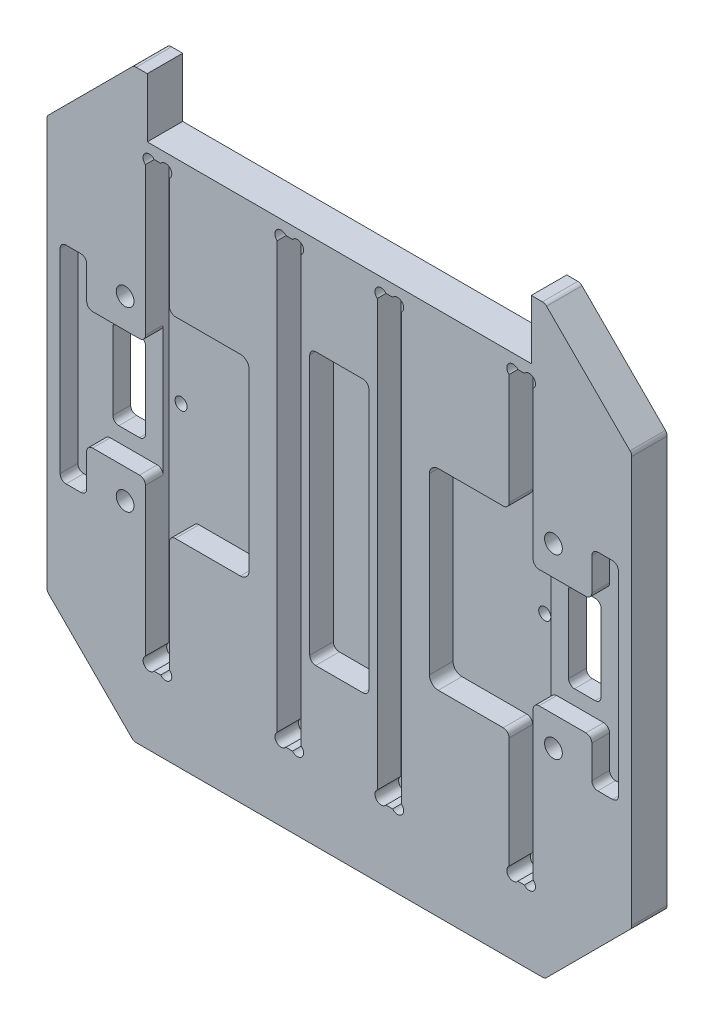
SolidWorks part; units mm, degrees
ref_plane "Front" through (0, 0, 0) normal (0, 0, 1) x (1, 0, 0)
ref_plane "Top" through (0, 0, 0) normal (0, 1, 0) x (1, 0, 0)
ref_plane "Right" through (0, 0, 0) normal (1, 0, 0) x (0, 0, -1)
sketch "Esquisse2" plane through (0, 0, 0) normal (0, 0, 1) x (1, 0, 0)
  line L1 (0, 0) -> (200, 0)
  line L2 (0, 0) -> (0, 200)
  line L3 (0, 200) -> (200, 200)
  line L4 (200, 0) -> (200, 200)
  dimension "D1" = 200
  dimension "D2" = 200
extrude "Boss.-Extru.1" add sketch "Esquisse2" along normal blind 12
chamfer "Chanfrein1" distance 30 distance2 30 4 edges at (0, 200, 6) (200, 200, 6) (200, 0, 6) (0, 0, 6)
sketch "Esquisse3" plane through (0, 0, 12) normal (0, 0, 1) x (1, 0, 0)
  line L0 (0, 100) -> (200, 100) construction
  line L1 (0, 170) -> (0, 30) construction
  line L2 (200, 30) -> (200, 170) construction
  line L3 (30, 0) -> (170, 0) construction
  line L4 (100, 100) -> (100, 198.2097) construction
  line L5 (185.5, 67) -> (185.5, 133)
  line L6 (187.5, 135) -> (192.5, 135)
  line L7 (194.5, 133) -> (194.5, 67)
  line L8 (187.5, 65) -> (192.5, 65)
  line L9 (12.5, 65) -> (7.5, 65)
  line L10 (5.5, 133) -> (5.5, 67)
  line L11 (12.5, 135) -> (7.5, 135)
  line L12 (14.5, 67) -> (14.5, 133)
  line L13 (69.5, 70.5) -> (69.5, 129.5)
  line L14 (66.5, 132.5) -> (45.5, 132.5)
  line L15 (42.5, 129.5) -> (42.5, 70.5)
  line L16 (190, 135) -> (190, 163.9784) construction
  line L17 (190, 163.9784) -> (100, 163.9784) construction
  line L18 (56, 132.5) -> (56, 150.9164) construction
  line L19 (56, 150.9164) -> (100, 150.9164) construction
  line L20 (66.5, 67.5) -> (45.5, 67.5)
  line L21 (133.5, 67.5) -> (154.5, 67.5)
  line L22 (157.5, 129.5) -> (157.5, 70.5)
  line L23 (133.5, 132.5) -> (154.5, 132.5)
  line L24 (130.5, 70.5) -> (130.5, 129.5)
  circle A0 centre (172.5, 130) radius 3
  circle A1 centre (172.5, 70) radius 3
  circle A2 centre (27.5, 70) radius 3
  circle A3 centre (27.5, 130) radius 3
  arc A4 (192.5, 65) -> (194.5, 67) centre (192.5, 67) ccw
  arc A5 (187.5, 65) -> (185.5, 67) centre (187.5, 67) cw
  arc A6 (192.5, 135) -> (194.5, 133) centre (192.5, 133) cw
  arc A7 (185.5, 133) -> (187.5, 135) centre (187.5, 133) cw
  arc A8 (12.5, 65) -> (14.5, 67) centre (12.5, 67) ccw
  arc A9 (7.5, 65) -> (5.5, 67) centre (7.5, 67) cw
  arc A10 (12.5, 135) -> (14.5, 133) centre (12.5, 133) cw
  arc A11 (5.5, 133) -> (7.5, 135) centre (7.5, 133) cw
  arc A12 (133.5, 67.5) -> (130.5, 70.5) centre (133.5, 70.5) cw
  arc A13 (154.5, 67.5) -> (157.5, 70.5) centre (154.5, 70.5) ccw
  arc A14 (157.5, 129.5) -> (154.5, 132.5) centre (154.5, 129.5) ccw
  arc A15 (133.5, 132.5) -> (130.5, 129.5) centre (133.5, 129.5) ccw
  arc A16 (66.5, 67.5) -> (69.5, 70.5) centre (66.5, 70.5) ccw
  arc A17 (45.5, 67.5) -> (42.5, 70.5) centre (45.5, 70.5) cw
  arc A18 (69.5, 129.5) -> (66.5, 132.5) centre (66.5, 129.5) ccw
  arc A19 (45.5, 132.5) -> (42.5, 129.5) centre (45.5, 129.5) ccw
  point P23 (194.5, 100)
  point P24 (185.5, 100)
  point P28 (14.5, 100)
  point P29 (5.5, 100)
  point P41 (42.5, 100)
  point P42 (69.5, 100)
  point P46 (130.5, 100)
  point P47 (157.5, 100)
  point P50 (194.5, 65)
  point P53 (185.5, 65)
  point P56 (194.5, 135)
  point P59 (185.5, 135)
  point P62 (14.5, 65)
  point P65 (5.5, 65)
  point P68 (14.5, 135)
  point P71 (5.5, 135)
  point P74 (130.5, 67.5)
  point P77 (157.5, 67.5)
  point P80 (157.5, 132.5)
  point P83 (130.5, 132.5)
  point P86 (69.5, 67.5)
  point P89 (42.5, 67.5)
  point P92 (69.5, 132.5)
  point P95 (42.5, 132.5)
  dimension "D2" = 60
  dimension "D3" = 44
  dimension "D4" = 6
  dimension "D11" = 2
  dimension "D12" = 3
  dimension "D1" = 100
  dimension "D5" = 9
  dimension "D6" = 13
  dimension "D7" = 70
  dimension "D8" = 90
  dimension "D9" = 65
  dimension "D10" = 27
extrude "Enlèv. mat.-Extru.1" cut sketch "Esquisse3" against normal through all both and the other way through all
sketch "Esquisse4" plane through (0, 0, 12) normal (0, 0, 1) x (1, 0, 0)
  line L16 (169.5858, 199) -> (30.4142, 199)
  line L17 (30.4142, 199) -> (1, 169.5858)
  line L18 (1, 169.5858) -> (1, 30.4142)
  line L19 (1, 30.4142) -> (30.4142, 1)
  line L20 (30.4142, 1) -> (169.5858, 1)
  line L21 (169.5858, 1) -> (199, 30.4142)
  line L22 (199, 30.4142) -> (199, 169.5858)
  line L23 (199, 169.5858) -> (169.5858, 199)
  line L24 (169.5858, 199) -> (30.4142, 199)
  line L25 (30.4142, 199) -> (1, 169.5858)
  line L26 (1, 169.5858) -> (1, 30.4142)
  line L27 (1, 30.4142) -> (30.4142, 1)
  line L28 (30.4142, 1) -> (169.5858, 1)
  line L29 (169.5858, 1) -> (199, 30.4142)
  line L30 (199, 30.4142) -> (199, 169.5858)
  line L31 (199, 169.5858) -> (169.5858, 199)
  line L32 (170, 200) -> (30, 200)
  line L33 (30, 200) -> (0, 170)
  line L34 (0, 170) -> (0, 30)
  line L35 (0, 30) -> (30, 0)
  line L36 (30, 0) -> (170, 0)
  line L37 (170, 0) -> (200, 30)
  line L38 (200, 30) -> (200, 170)
  line L39 (200, 170) -> (170, 200)
  line L40 (170, 200) -> (30, 200)
  line L41 (30, 200) -> (0, 170)
  line L42 (0, 170) -> (0, 30)
  line L43 (0, 30) -> (30, 0)
  line L44 (30, 0) -> (170, 0)
  line L45 (170, 0) -> (200, 30)
  line L46 (200, 30) -> (200, 170)
  line L47 (200, 170) -> (170, 200)
  dimension "D1" = 1
  dimension "D2" = 0
extrude "Enlèv. mat.-Extru.2" cut sketch "Esquisse4" against normal blind 10
sketch "Esquisse5" plane through (0, 0, 12) normal (0, 0, 1) x (1, 0, 0)
  line L0 (100, 0) -> (100, 100) construction
  line L1 (14.5, 120) -> (14.5, 80)
  line L2 (165.5, 120) -> (185.5, 120)
  line L3 (165.5, 120) -> (165.5, 80)
  line L4 (165.5, 80) -> (185.5, 80)
  line L5 (30, 0) -> (170, 0) construction
  line L6 (100, 100) -> (165.5, 100) construction
  line L7 (185.5, 120) -> (185.5, 80)
  line L8 (100, 100) -> (69.5, 100) construction
  line L9 (69.5, 70.5) -> (69.5, 129.5) construction
  line L10 (34.5, 80) -> (14.5, 80)
  line L11 (34.5, 120) -> (34.5, 80)
  line L12 (34.5, 120) -> (14.5, 120)
  dimension "D1" = 40
  dimension "D2" = 65.5
  dimension "D3" = 20
extrude "Enlèv. mat.-Extru.3" cut sketch "Esquisse5" against normal blind 6
sketch "Esquisse6" plane through (0, 0, 12) normal (0, 0, 1) x (1, 0, 0)
  line L0 (69.5, 100) -> (130.5, 100) construction
  line L1 (157.5, 175) -> (165.62, 175)
  line L2 (157.5, 175) -> (157.5, 25)
  line L3 (157.5, 25) -> (165.62, 25)
  line L4 (165.62, 175) -> (165.62, 25)
  line L5 (69.5, 70.5) -> (69.5, 129.5) construction
  line L6 (130.5, 129.5) -> (130.5, 70.5) construction
  line L7 (100, 100) -> (100, 191.362) construction
  line L8 (130.5, 100) -> (157.5, 100) construction
  line L9 (157.5, 70.5) -> (157.5, 129.5) construction
  line L10 (34.38, 175) -> (34.38, 25)
  line L11 (42.5, 25) -> (34.38, 25)
  line L12 (42.5, 175) -> (42.5, 25)
  line L13 (42.5, 175) -> (34.38, 175)
  line L14 (112.88, 100) -> (100, 100) construction
  line L15 (112.88, 175) -> (121, 175)
  line L16 (112.88, 175) -> (112.88, 25)
  line L17 (112.88, 25) -> (121, 25)
  line L18 (121, 175) -> (121, 25)
  line L19 (79, 175) -> (79, 25)
  line L20 (87.12, 25) -> (79, 25)
  line L21 (87.12, 175) -> (87.12, 25)
  line L22 (87.12, 175) -> (79, 175)
  dimension "D1" = 150
  dimension "D2" = 8.12
  dimension "D3" = 8.12
  dimension "D4" = 150
  dimension "D5" = 21
extrude "Enlèv. mat.-Extru.4" cut sketch "Esquisse6" against normal blind 8
sketch "Esquisse7" plane through (0, 0, 12) normal (0, 0, 1) x (1, 0, 0)
  line L0 (87.12, 100) -> (112.88, 100) construction
  line L1 (87.12, 25) -> (87.12, 175) construction
  line L2 (112.88, 175) -> (112.88, 25) construction
  line L3 (100, 100) -> (100, 199) construction
  line L4 (169.5858, 199) -> (30.4142, 199) construction
  line L5 (114.18, 173.7) -> (112.88, 175) construction
  line L6 (121, 175) -> (112.88, 175) construction
  line L7 (116.94, 175) -> (116.94, 100) construction
  line L8 (121, 175) -> (112.88, 175) construction
  line L9 (116.94, 100) -> (112.88, 100) construction
  line L10 (119.7, 173.7) -> (121, 175) construction
  line L11 (119.7, 26.3) -> (121, 25) construction
  line L12 (114.18, 26.3) -> (112.88, 25) construction
  line L13 (116.94, 100) -> (139.25, 100) construction
  line L14 (139.25, 100) -> (139.25, 192.3771) construction
  line L15 (164.32, 26.3) -> (165.62, 25) construction
  line L16 (158.8, 26.3) -> (157.5, 25) construction
  line L17 (158.8, 173.7) -> (157.5, 175) construction
  line L18 (161.56, 100) -> (165.62, 100) construction
  line L19 (161.56, 175) -> (161.56, 100) construction
  line L20 (164.32, 173.7) -> (165.62, 175) construction
  line L21 (165.62, 175) -> (157.5, 175) construction
  line L22 (35.68, 173.7) -> (34.38, 175) construction
  line L23 (38.44, 175) -> (38.44, 100) construction
  line L24 (38.44, 100) -> (34.38, 100) construction
  line L25 (41.2, 173.7) -> (42.5, 175) construction
  line L26 (41.2, 26.3) -> (42.5, 25) construction
  line L27 (35.68, 26.3) -> (34.38, 25) construction
  line L28 (60.75, 100) -> (60.75, 192.3771) construction
  line L29 (83.06, 100) -> (60.75, 100) construction
  line L30 (85.82, 26.3) -> (87.12, 25) construction
  line L31 (80.3, 26.3) -> (79, 25) construction
  line L32 (80.3, 173.7) -> (79, 175) construction
  line L33 (83.06, 100) -> (87.12, 100) construction
  line L34 (83.06, 175) -> (83.06, 100) construction
  line L35 (85.82, 173.7) -> (87.12, 175) construction
  circle A0 centre (114.18, 173.7) radius 2.1
  circle A1 centre (119.7, 173.7) radius 2.1
  circle A2 centre (119.7, 26.3) radius 2.1
  circle A3 centre (114.18, 26.3) radius 2.1
  circle A4 centre (164.32, 26.3) radius 2.1
  circle A5 centre (158.8, 26.3) radius 2.1
  circle A6 centre (158.8, 173.7) radius 2.1
  circle A7 centre (164.32, 173.7) radius 2.1
  circle A8 centre (35.68, 173.7) radius 2.1
  circle A9 centre (41.2, 173.7) radius 2.1
  circle A10 centre (41.2, 26.3) radius 2.1
  circle A11 centre (35.68, 26.3) radius 2.1
  circle A12 centre (85.82, 26.3) radius 2.1
  circle A13 centre (80.3, 26.3) radius 2.1
  circle A14 centre (80.3, 173.7) radius 2.1
  circle A15 centre (85.82, 173.7) radius 2.1
  dimension "D1" = 4.2
  dimension "D2" = 1.3
  dimension "D3" = 1.3
extrude "Enlèv. mat.-Extru.5" cut sketch "Esquisse7" against normal up to vertex (8 mm away) up to point (112.88, 25, 4)
sketch "Esquisse8" plane through (0, 0, 12) normal (0, 0, 1) x (1, 0, 0)
  line L0 (100, 1) -> (100, 199) construction
  line L1 (30.4142, 1) -> (169.5858, 1) construction
  line L2 (169.5858, 199) -> (30.4142, 199) construction
  line L3 (100, 100) -> (252.8445, 100) construction
  line L4 (110, 54) -> (110, 146)
  line L5 (110, 146) -> (90, 146)
  line L6 (90, 54) -> (90, 146)
  line L7 (110, 54) -> (90, 54)
  point P8 (100, 54)
  point P12 (100, 146)
  point P14 (90, 100)
  point P15 (110, 100)
  dimension "D1" = 20
  dimension "D2" = 92
extrude "Enlèv. mat.-Extru.6" cut sketch "Esquisse8" against normal blind 8
sketch "Esquisse10" plane through (0, 0, 12) normal (0, 0, 1) x (1, 0, 0)
  line L0 (45.5, 132.5) -> (42.5, 132.5)
  line L1 (42.5, 129.5) -> (42.5, 172.0508) construction
  line L2 (42.5, 132.5) -> (42.5, 129.5)
  line L3 (42.5, 129.5) -> (45.5, 132.5)
  line L4 (42.5, 100) -> (69.5, 100) construction
  line L5 (42.5, 70.5) -> (42.5, 129.5) construction
  line L6 (69.5, 70.5) -> (69.5, 129.5) construction
  line L7 (100, 54) -> (100, 146) construction
  line L8 (90, 54) -> (110, 54) construction
  line L9 (110, 146) -> (90, 146) construction
  line L10 (42.5, 70.5) -> (45.5, 67.5)
  line L11 (42.5, 67.5) -> (42.5, 70.5)
  line L12 (45.5, 67.5) -> (42.5, 67.5)
  line L13 (154.5, 67.5) -> (157.5, 67.5)
  line L14 (157.5, 67.5) -> (157.5, 70.5)
  line L15 (157.5, 70.5) -> (154.5, 67.5)
  line L16 (157.5, 129.5) -> (154.5, 132.5)
  line L17 (157.5, 132.5) -> (157.5, 129.5)
  line L18 (154.5, 132.5) -> (157.5, 132.5)
extrude "Enlèv. mat.-Extru.8" cut sketch "Esquisse10" against normal up to vertex
sketch "Esquisse11" plane through (0, 0, 6) normal (0, 0, 1) x (1, 0, 0)
  line L0 (28.38, 100) -> (34.38, 100) construction
  line L1 (17.38, 115) -> (28.38, 115)
  line L2 (17.38, 115) -> (17.38, 85)
  line L3 (17.38, 85) -> (28.38, 85)
  line L4 (28.38, 115) -> (28.38, 85)
  line L5 (34.38, 120) -> (34.38, 80) construction
  line L6 (100, 1) -> (100, 159.2856) construction
  line L7 (30.4142, 1) -> (169.5858, 1) construction
  line L8 (171.62, 115) -> (171.62, 85)
  line L9 (182.62, 85) -> (171.62, 85)
  line L10 (182.62, 115) -> (182.62, 85)
  line L11 (182.62, 115) -> (171.62, 115)
  dimension "D1" = 6
  dimension "D2" = 11
  dimension "D3" = 30
extrude "Enlèv. mat.-Extru.9" cut sketch "Esquisse11" against normal through all both and the other way through all
fillet "Congé1" radius 2 16 edges at (110, 54, 8) (90, 54, 8) (110, 146, 8) (90, 146, 8) (165.62, 120, 9) (185.5, 120, 9) (185.5, 80, 9) (165.62, 80, 9) (34.38, 80, 9) (14.5, 80, 9) (34.38, 120, 9) (14.5, 120, 9) (42.5, 67.5, 8) (42.5, 132.5, 8) (157.5, 132.5, 8) (157.5, 67.5, 8)
fillet "Congé2" radius 2 16 edges at (1, 169.5858, 7) (30.4142, 199, 7) (169.5858, 199, 7) (199, 169.5858, 7) (199, 30.4142, 7) (169.5858, 1, 7) (1, 30.4142, 7) (30.4142, 1, 7) (170, 200, 1) (200, 170, 1) (200, 30, 1) (170, 0, 1) (30, 0, 1) (0, 30, 1) (0, 170, 1) (30, 200, 1)
sketch "Esquisse9" plane through (0, 0, 12) normal (0, 0, 1) x (1, 0, 0)
  line L0 (22.7574, 205.4853) -> (-5.4853, 177.2426)
  line L1 (-9, 168.7574) -> (-9, 31.2426)
  line L2 (-5.4853, 22.7574) -> (22.7574, -5.4853)
  line L3 (31.2426, -9) -> (168.7574, -9)
  line L4 (177.2426, -5.4853) -> (205.4853, 22.7574)
  line L5 (209, 31.2426) -> (209, 168.7574)
  line L6 (205.4853, 177.2426) -> (177.2426, 205.4853)
  line L7 (168.7574, 209) -> (31.2426, 209)
  line L8 (29.8284, 198.4142) -> (1.5858, 170.1716)
  line L9 (1, 168.7574) -> (1, 31.2426)
  line L10 (1.5858, 29.8284) -> (29.8284, 1.5858)
  line L11 (31.2426, 1) -> (168.7574, 1)
  line L12 (170.1716, 1.5858) -> (198.4142, 29.8284)
  line L13 (199, 31.2426) -> (199, 168.7574)
  line L14 (198.4142, 170.1716) -> (170.1716, 198.4142)
  line L15 (168.7574, 199) -> (31.2426, 199)
  line L16 (29.8284, 198.4142) -> (1.5858, 170.1716)
  line L17 (1, 168.7574) -> (1, 31.2426)
  line L18 (1.5858, 29.8284) -> (29.8284, 1.5858)
  line L19 (31.2426, 1) -> (168.7574, 1)
  line L20 (170.1716, 1.5858) -> (198.4142, 29.8284)
  line L21 (199, 31.2426) -> (199, 168.7574)
  line L22 (198.4142, 170.1716) -> (170.1716, 198.4142)
  line L23 (168.7574, 199) -> (31.2426, 199)
  arc A0 (-5.4853, 177.2426) -> (-9, 168.7574) centre (3, 168.7574) ccw
  arc A1 (-9, 31.2426) -> (-5.4853, 22.7574) centre (3, 31.2426) ccw
  arc A2 (22.7574, -5.4853) -> (31.2426, -9) centre (31.2426, 3) ccw
  arc A3 (168.7574, -9) -> (177.2426, -5.4853) centre (168.7574, 3) ccw
  arc A4 (205.4853, 22.7574) -> (209, 31.2426) centre (197, 31.2426) ccw
  arc A5 (209, 168.7574) -> (205.4853, 177.2426) centre (197, 168.7574) ccw
  arc A6 (177.2426, 205.4853) -> (168.7574, 209) centre (168.7574, 197) ccw
  arc A7 (31.2426, 209) -> (22.7574, 205.4853) centre (31.2426, 197) ccw
  arc A8 (1.5858, 170.1716) -> (1, 168.7574) centre (3, 168.7574) ccw
  arc A9 (1, 31.2426) -> (1.5858, 29.8284) centre (3, 31.2426) ccw
  arc A10 (29.8284, 1.5858) -> (31.2426, 1) centre (31.2426, 3) ccw
  arc A11 (168.7574, 1) -> (170.1716, 1.5858) centre (168.7574, 3) ccw
  arc A12 (198.4142, 29.8284) -> (199, 31.2426) centre (197, 31.2426) ccw
  arc A13 (199, 168.7574) -> (198.4142, 170.1716) centre (197, 168.7574) ccw
  arc A14 (170.1716, 198.4142) -> (168.7574, 199) centre (168.7574, 197) ccw
  arc A15 (31.2426, 199) -> (29.8284, 198.4142) centre (31.2426, 197) ccw
  arc A16 (1.5858, 170.1716) -> (1, 168.7574) centre (3, 168.7574) ccw
  arc A17 (1, 31.2426) -> (1.5858, 29.8284) centre (3, 31.2426) ccw
  arc A18 (29.8284, 1.5858) -> (31.2426, 1) centre (31.2426, 3) ccw
  arc A19 (168.7574, 1) -> (170.1716, 1.5858) centre (168.7574, 3) ccw
  arc A20 (198.4142, 29.8284) -> (199, 31.2426) centre (197, 31.2426) ccw
  arc A21 (199, 168.7574) -> (198.4142, 170.1716) centre (197, 168.7574) ccw
  arc A22 (170.1716, 198.4142) -> (168.7574, 199) centre (168.7574, 197) ccw
  arc A23 (31.2426, 199) -> (29.8284, 198.4142) centre (31.2426, 197) ccw
  dimension "D1" = 0
  dimension "D2" = 10
extrude "Enlèv. mat.-Extru.7" cut sketch "Esquisse9" against normal through all both and the other way through all
fillet "Congé3" radius 2 8 edges at (182.62, 85, 3) (171.62, 85, 3) (182.62, 115, 3) (171.62, 115, 3) (17.38, 115, 3) (28.38, 115, 3) (28.38, 85, 3) (17.38, 85, 3)
sketch "Esquisse12" plane through (0, 0, 0) normal (0, 0, -1) x (-1, 0, 0)
  line L0 (-69.5, 70.5) -> (-69.5, 129.5) construction
  line L1 (-66.5, 132.5) -> (-45.5, 132.5) construction
  line L2 (-42.5, 129.5) -> (-42.5, 70.5) construction
  line L3 (-45.5, 67.5) -> (-66.5, 67.5) construction
  line L4 (-133.5, 67.5) -> (-154.5, 67.5) construction
  line L5 (-130.5, 129.5) -> (-130.5, 70.5) construction
  line L6 (-154.5, 132.5) -> (-133.5, 132.5) construction
  line L7 (-157.5, 70.5) -> (-157.5, 129.5) construction
  line L8 (-69.5, 70.5) -> (-69.5, 129.5)
  line L9 (-66.5, 132.5) -> (-45.5, 132.5)
  line L10 (-42.5, 129.5) -> (-42.5, 70.5)
  line L11 (-45.5, 67.5) -> (-66.5, 67.5)
  line L12 (-133.5, 67.5) -> (-154.5, 67.5)
  line L13 (-130.5, 129.5) -> (-130.5, 70.5)
  line L14 (-154.5, 132.5) -> (-133.5, 132.5)
  line L15 (-157.5, 70.5) -> (-157.5, 129.5)
  arc A0 (-66.5, 132.5) -> (-69.5, 129.5) centre (-66.5, 129.5) ccw construction
  arc A1 (-42.5, 129.5) -> (-45.5, 132.5) centre (-45.5, 129.5) ccw construction
  arc A2 (-45.5, 67.5) -> (-42.5, 70.5) centre (-45.5, 70.5) ccw construction
  arc A3 (-69.5, 70.5) -> (-66.5, 67.5) centre (-66.5, 70.5) ccw construction
  arc A4 (-157.5, 70.5) -> (-154.5, 67.5) centre (-154.5, 70.5) ccw construction
  arc A5 (-133.5, 67.5) -> (-130.5, 70.5) centre (-133.5, 70.5) ccw construction
  arc A6 (-130.5, 129.5) -> (-133.5, 132.5) centre (-133.5, 129.5) ccw construction
  arc A7 (-154.5, 132.5) -> (-157.5, 129.5) centre (-154.5, 129.5) ccw construction
  arc A8 (-66.5, 132.5) -> (-69.5, 129.5) centre (-66.5, 129.5) ccw
  arc A9 (-42.5, 129.5) -> (-45.5, 132.5) centre (-45.5, 129.5) ccw
  arc A10 (-45.5, 67.5) -> (-42.5, 70.5) centre (-45.5, 70.5) ccw
  arc A11 (-69.5, 70.5) -> (-66.5, 67.5) centre (-66.5, 70.5) ccw
  arc A12 (-157.5, 70.5) -> (-154.5, 67.5) centre (-154.5, 70.5) ccw
  arc A13 (-133.5, 67.5) -> (-130.5, 70.5) centre (-133.5, 70.5) ccw
  arc A14 (-130.5, 129.5) -> (-133.5, 132.5) centre (-133.5, 129.5) ccw
  arc A15 (-154.5, 132.5) -> (-157.5, 129.5) centre (-154.5, 129.5) ccw
extrude "Boss.-Extru.2" add sketch "Esquisse12" against normal up to vertex (4 mm away) up to point (157.5, 129.5, 4)
sketch "Esquisse13" plane through (0, 0, 0) normal (0, 0, -1) x (-1, 0, 0)
  line L0 (-14.5, 67) -> (-14.5, 133) construction
  line L1 (-12.5, 135) -> (-7.5, 135) construction
  line L2 (-5.5, 133) -> (-5.5, 67) construction
  line L3 (-7.5, 65) -> (-12.5, 65) construction
  line L4 (-187.5, 65) -> (-192.5, 65) construction
  line L5 (-194.5, 67) -> (-194.5, 133) construction
  line L6 (-192.5, 135) -> (-187.5, 135) construction
  line L7 (-185.5, 133) -> (-185.5, 67) construction
  line L8 (-14.5, 67) -> (-14.5, 133)
  line L9 (-12.5, 135) -> (-7.5, 135)
  line L10 (-5.5, 133) -> (-5.5, 67)
  line L11 (-7.5, 65) -> (-12.5, 65)
  line L12 (-187.5, 65) -> (-192.5, 65)
  line L13 (-194.5, 67) -> (-194.5, 133)
  line L14 (-192.5, 135) -> (-187.5, 135)
  line L15 (-185.5, 133) -> (-185.5, 67)
  arc A0 (-14.5, 67) -> (-12.5, 65) centre (-12.5, 67) ccw construction
  arc A1 (-12.5, 135) -> (-14.5, 133) centre (-12.5, 133) ccw construction
  arc A2 (-5.5, 133) -> (-7.5, 135) centre (-7.5, 133) ccw construction
  arc A3 (-7.5, 65) -> (-5.5, 67) centre (-7.5, 67) ccw construction
  arc A4 (-187.5, 65) -> (-185.5, 67) centre (-187.5, 67) ccw construction
  arc A5 (-194.5, 67) -> (-192.5, 65) centre (-192.5, 67) ccw construction
  arc A6 (-192.5, 135) -> (-194.5, 133) centre (-192.5, 133) ccw construction
  arc A7 (-185.5, 133) -> (-187.5, 135) centre (-187.5, 133) ccw construction
  arc A8 (-14.5, 67) -> (-12.5, 65) centre (-12.5, 67) ccw
  arc A9 (-12.5, 135) -> (-14.5, 133) centre (-12.5, 133) ccw
  arc A10 (-5.5, 133) -> (-7.5, 135) centre (-7.5, 133) ccw
  arc A11 (-7.5, 65) -> (-5.5, 67) centre (-7.5, 67) ccw
  arc A12 (-187.5, 65) -> (-185.5, 67) centre (-187.5, 67) ccw
  arc A13 (-194.5, 67) -> (-192.5, 65) centre (-192.5, 67) ccw
  arc A14 (-192.5, 135) -> (-194.5, 133) centre (-192.5, 133) ccw
  arc A15 (-185.5, 133) -> (-187.5, 135) centre (-187.5, 133) ccw
extrude "Boss.-Extru.3" add sketch "Esquisse13" against normal up to vertex (6 mm away) up to point (14.5, 78, 6)
sketch "Esquisse14" plane through (0, 0, 4) normal (0, 0, 1) x (1, 0, 0)
  line L0 (100, 54) -> (100, 146) construction
  line L1 (92, 54) -> (108, 54) construction
  line L2 (108, 146) -> (92, 146) construction
  line L3 (100, 100) -> (-15.2006, 100) construction
  line L4 (83.06, 160) -> (83.06, 175) construction
  line L5 (84.1708, 175) -> (81.9492, 175) construction
  line L7 (79, 150.5938) -> (42.5, 150.5938) construction
  line L8 (79, 172.0508) -> (79, 27.9492) construction
  line L9 (42.5, 134.5) -> (42.5, 172.0508) construction
  line L10 (60.75, 150.5938) -> (60.75, 164.7943) construction
  line L11 (83.06, 100) -> (83.06, 40) construction
  line L12 (38.44, 100) -> (38.44, 40) construction
  line L13 (38.44, 160) -> (38.44, 175) construction
  line L14 (161.56, 160) -> (161.56, 175) construction
  line L15 (161.56, 100) -> (161.56, 40) construction
  line L16 (116.94, 100) -> (116.94, 40) construction
  line L17 (139.25, 150.5938) -> (139.25, 164.7943) construction
  line L18 (121, 150.5938) -> (157.5, 150.5938) construction
  line L19 (116.94, 160) -> (116.94, 175) construction
  circle A0 centre (83.06, 160) radius 2.05
  circle A1 centre (83.06, 40) radius 2.05
  circle A2 centre (83.06, 100) radius 2.05
  circle A3 centre (38.44, 100) radius 2.05
  circle A4 centre (38.44, 40) radius 2.05
  circle A5 centre (38.44, 160) radius 2.05
  circle A6 centre (161.56, 160) radius 2.05
  circle A7 centre (161.56, 40) radius 2.05
  circle A8 centre (161.56, 100) radius 2.05
  circle A9 centre (116.94, 100) radius 2.05
  circle A10 centre (116.94, 40) radius 2.05
  circle A11 centre (116.94, 160) radius 2.05
  dimension "D1" = 60
  dimension "D2" = 4.1
extrude "Enlèv. mat.-Extru.10" cut sketch "Esquisse14" against normal through all both and the other way through all
sketch "Esquisse15" plane through (0, 0, 12) normal (0, 0, 1) x (1, 0, 0)
  line L0 (100, 199) -> (100, 189) construction
  line L1 (168.7574, 199) -> (31.2426, 199) construction
  line L3 (35, 179) -> (165, 179)
  line L4 (35, 179) -> (35, 199)
  line L5 (35, 199) -> (165, 199)
  line L6 (165, 179) -> (165, 199)
  line L7 (35, 179) -> (165, 199) construction
  line L8 (35, 199) -> (165, 179) construction
  dimension "D1" = 20
  dimension "D2" = 130
extrude "Enlèv. mat.-Extru.11" cut sketch "Esquisse15" against normal through all both and the other way through all
sketch "Esquisse16" [suppressed] plane through (0, 0, 12) normal (0, 0, 1) x (1, 0, 0)
  line L0 (169.1716, 200) -> (30.8284, 200) construction
  line L1 (40, 199) -> (160, 199)
  line L2 (40, 199) -> (40, 200)
  line L3 (40, 200) -> (160, 200)
  line L4 (160, 199) -> (160, 200)
  line L5 (160, 199) -> (160, 179) construction
extrude "Enlèv. mat.-Extru.12" [suppressed] cut sketch "Esquisse16" against normal through all both and the other way through all
